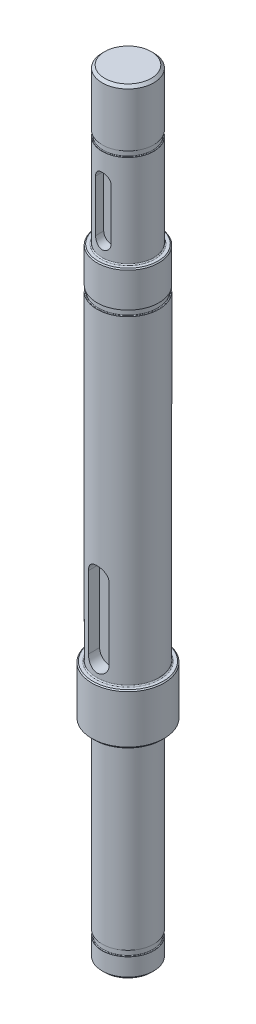
SolidWorks part; units mm, degrees
ref_plane "Front" through (0, 0, 0) normal (0, 0, 1) x (1, 0, 0)
ref_plane "Top" through (0, 0, 0) normal (0, 1, 0) x (1, 0, 0)
ref_plane "Right" through (0, 0, 0) normal (1, 0, 0) x (0, 0, -1)
sketch "Sketch2" plane through (0, 0, 0) normal (1, 0, 0) x (0, 0, -1)
  line L0 (0, 58.3723) -> (0, -41.9724) construction
  line L1 (0, 0) -> (5, 0)
  line L2 (5, 0) -> (5, 40)
  line L3 (5, 40) -> (7, 40)
  line L4 (7, 40) -> (7, 50)
  line L5 (7, 50) -> (6, 50)
  line L6 (6, 50) -> (6, 120)
  line L7 (6, 120) -> (5, 120)
  line L8 (5, 120) -> (5, 150)
  line L9 (5, 150) -> (0, 150)
  line L10 (0, 150) -> (0, 0)
  dimension "D2" = 5
  dimension "D3" = 2
  dimension "D4" = 1
  dimension "D5" = 70
  dimension "D6" = 40
  dimension "D7" = 10
  dimension "D8" = 30
revolve "Revolve1" add sketch "Sketch2" angle 360 about L10
ref_plane "Plane1" through (0, 120, 0) normal (-1, 0, 0) x (0, 0, 1)
sketch "Sketch4" plane through (0, 120, 0) normal (-1, 0, 0) x (0, 0, 1)
  line L0 (4.91, -116.1) -> (6, -116.1)
  line L1 (6, -116.1) -> (6, -115)
  line L2 (6, -115) -> (4.91, -115)
  line L3 (4.8, -115.11) -> (4.8, -115.99)
  line L4 (0, -50) -> (0, 50) construction
  line L5 (-5, -80) -> (5, -80) construction
  arc A0 (4.8, -115.99) -> (4.91, -116.1) centre (4.91, -115.99) ccw
  arc A1 (4.8, -115.11) -> (4.91, -115) centre (4.91, -115.11) cw
  dimension "D1" = 0.11
  dimension "D2" = 0.11
  dimension "D3" = 35
  dimension "D4" = 1.1
  dimension "D5" = 1.09
  dimension "D6" = 4.8
revolve "Groove for BS 3673 P4 - S010M, External Circlip1" cut sketch "Sketch4"
ref_plane "Plane2" through (0, 120, 0) normal (-1, 0, 0) x (0, 0, 1)
sketch "Sketch6" plane through (0, 120, 0) normal (-1, 0, 0) x (0, 0, 1)
  line L0 (4.91, 18) -> (6, 18)
  line L1 (6, 18) -> (6, 19.1)
  line L2 (6, 19.1) -> (4.91, 19.1)
  line L3 (4.8, 18.99) -> (4.8, 18.11)
  line L4 (0, -50) -> (0, 50) construction
  line L5 (5, 0) -> (-5, 0) construction
  arc A0 (4.8, 18.11) -> (4.91, 18) centre (4.91, 18.11) ccw
  arc A1 (4.8, 18.99) -> (4.91, 19.1) centre (4.91, 18.99) cw
  dimension "D1" = 0.11
  dimension "D2" = 0.11
  dimension "D3" = 18
  dimension "D4" = 1.1
  dimension "D5" = 4.8
  dimension "D6" = 1.09
revolve "Groove for BS 3673 P4 - S010M, External Circlip2" cut sketch "Sketch6" angle 360 about L4
ref_plane "Plane3" through (0, 118, 0) normal (-1, 0, 0) x (0, 0, 1)
sketch "Sketch8" plane through (0, 118, 0) normal (-1, 0, 0) x (0, 0, 1)
  line L0 (5.86, -6) -> (7.2, -6)
  line L1 (7.2, -6) -> (7.2, -4.9)
  line L2 (7.2, -4.9) -> (5.86, -4.9)
  line L3 (5.75, -5.01) -> (5.75, -5.89)
  line L4 (0, -50) -> (0, 50) construction
  line L6 (6, 2) -> (-6, 2) construction
  arc A0 (5.75, -5.89) -> (5.86, -6) centre (5.86, -5.89) ccw
  arc A1 (5.75, -5.01) -> (5.86, -4.9) centre (5.86, -5.01) cw
  dimension "D1" = 0.11
  dimension "D2" = 0.11
  dimension "D3" = 1.1
  dimension "D4" = 1.34
  dimension "D5" = 6.9
  dimension "D6" = 5.75
revolve "Groove for BS 3673 P4 - S012M, External Circlip1" cut sketch "Sketch8"
chamfer "Chamfer1" distance 0.5 angle 45 3 edges at (0, 40, 7) (0, 150, 5) (0, 0, 5)
chamfer "Chamfer2" distance 0.2 angle 45 2 edges at (0, 120, 6) (0, 50, 7)
fillet "Fillet1" radius 0.2 3 edges at (0, 50, 6) (0, 40, 5) (0, 120, 5)
ref_plane "Plane4" through (0, 0, 3.5) normal (0, 0, 1) x (1, 0, 0)
sketch "Sketch9" plane through (0, 0, 3.5) normal (0, 0, 1) x (1, 0, 0)
  line L0 (0, 53) -> (0, 67) construction
  line L1 (-2, 53) -> (-2, 67)
  line L2 (2, 53) -> (2, 67)
  line L3 (6.8, 50) -> (-6.8, 50) construction
  arc A0 (-2, 53) -> (2, 53) centre (0, 53) ccw
  arc A1 (2, 67) -> (-2, 67) centre (0, 67) ccw
  point P3 (0, 60)
  dimension "D3" = 2
  dimension "D1" = 10
  dimension "D2" = 14
extrude "Cut-Extrude1" cut sketch "Sketch9" along normal through all
ref_plane "Plane5" through (0, 0, 5) normal (0, 0, 1) x (1, 0, 0)
sketch "Sketch10" plane through (0, 0, 5) normal (0, 0, 1) x (1, 0, 0)
  line L0 (0, 123) -> (0, 133) construction
  line L1 (-1.5, 123) -> (-1.5, 133)
  line L2 (1.5, 123) -> (1.5, 133)
  line L3 (5.8, 120) -> (-5.8, 120) construction
  arc A0 (-1.5, 123) -> (1.5, 123) centre (0, 123) ccw
  arc A1 (1.5, 133) -> (-1.5, 133) centre (0, 133) ccw
  point P3 (0, 128)
  dimension "D1" = 1.5
  dimension "D2" = 10
  dimension "D3" = 8
extrude "Cut-Extrude2" cut sketch "Sketch10" against normal blind 1.8
